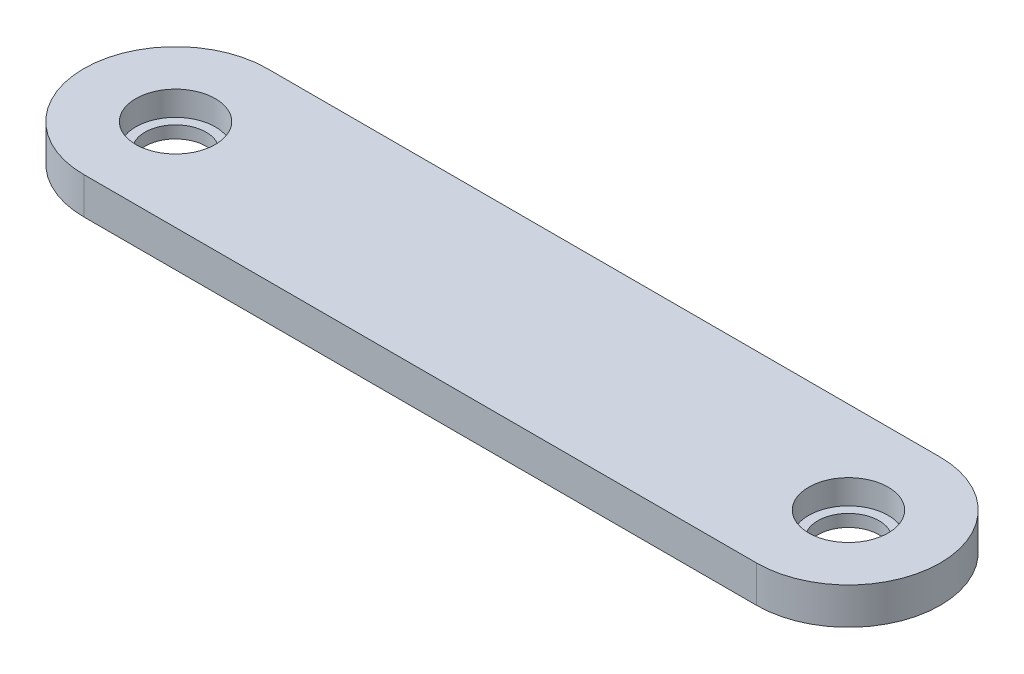
SolidWorks part; units mm, degrees
ref_plane "Front Plane" through (0, 0, 0) normal (0, 0, 1) x (1, 0, 0)
ref_plane "Top Plane" through (0, 0, 0) normal (0, 1, 0) x (1, 0, 0)
ref_plane "Right Plane" through (0, 0, 0) normal (1, 0, 0) x (0, 0, -1)
sketch "Sketch2" plane through (0, 0, 0) normal (0, 1, 0) x (1, 0, 0)
  line L1 (-45, 15) -> (65, 15)
  line L3 (-45, -15) -> (65, -15)
  arc A0 (-45, 15) -> (-45, -15) centre (-45, 0) ccw
  arc A1 (65, -15) -> (65, 15) centre (65, 0) ccw
  circle A2 centre (-45, 0) radius 5
  circle A3 centre (65, 0) radius 5
  point P0 (0, 0)
  point P7 (0, 0)
extrude "Boss-Extrude1" add sketch "Sketch2" along normal blind 6
sketch "Sketch3" plane through (0, 6, 0) normal (0, 1, 0) x (1, 0, 0)
  circle A0 centre (-45, 0) radius 6.5
  circle A1 centre (65, 0) radius 6.5
extrude "Cut-Extrude1" cut sketch "Sketch3" against normal blind 4
